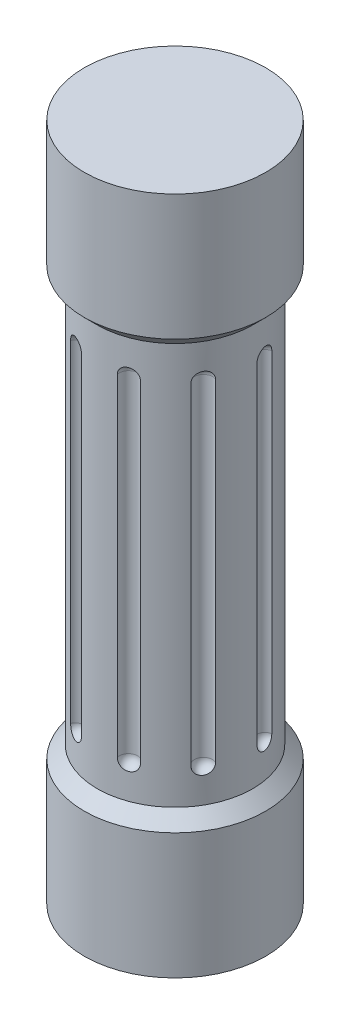
SolidWorks part; units mm, degrees
ref_plane "Front Plane" through (0, 0, 0) normal (0, 0, 1) x (1, 0, 0)
ref_plane "Top Plane" through (0, 0, 0) normal (0, 1, 0) x (1, 0, 0)
ref_plane "Right Plane" through (0, 0, 0) normal (1, 0, 0) x (0, 0, -1)
sketch "Sketch1" plane through (0, 0, 0) normal (0, 0, 1) x (1, 0, 0)
  line L0 (0, 0) -> (0, 26.2)
  line L1 (0, 26.2) -> (3.5, 26.2)
  line L2 (3.5, 26.2) -> (3.5, 23.35)
  line L3 (0, 0) -> (3.5, 0)
  line L4 (3.5, 0) -> (3.5, 2.85)
  line L5 (3.5, 2.85) -> (3.5, 4.85)
  line L6 (0, 26.2) -> (0, 52.4) construction
  line L8 (3, 20.85) -> (3, 5.35)
  line L10 (3, 13.1) -> (0, 13.1) construction
  line L11 (3.5, 23.35) -> (3.5, 21.35)
  line L12 (3.5, 21.35) -> (3.5, 4.85) construction
  line L13 (3.5, 21.35) -> (3, 20.85)
  line L14 (3.5, 4.85) -> (3, 5.35)
  point P3 (0, 13.1)
  dimension "D1" = 20.5
  dimension "D2" = 2.85
  dimension "D3" = 7
  dimension "D4" = 0.5
  dimension "D5" = 2
  dimension "D6" = 45
revolve "Main Support Pole" add sketch "Sketch1" angle 360 about L6
sketch "Sketch2" plane through (0, 0, 0) normal (1, 0, 0) x (0, 0, -1)
  line L0 (3, 19.85) -> (3, 6.35)
  line L3 (2.65, 19.5) -> (2.65, 6.7)
  line L9 (2.65, 13.1) -> (3, 13.1) construction
  line L10 (0, 0) -> (0, 26.2) construction
  line L11 (3.5, 26.2) -> (-3.5, 26.2) construction
  line L12 (3, 5.35) -> (3, 20.85) construction
  line L14 (3, 19.85) -> (3, 46.05) construction
  arc A2 (2.65, 19.5) -> (3, 19.85) centre (3, 19.5) cw
  arc A3 (2.65, 6.7) -> (3, 6.35) centre (3, 6.7) ccw
  point P8 (3, 13.1)
  point P14 (0, 13.1)
  dimension "D1" = 1
  dimension "D2" = 0.35
revolve "Column Cut" cut sketch "Sketch2" angle 360 about L14
pattern_circular "Column Circular Pattern Cut" count 9 over 360 about axis through (0, 0, 0) along (0, 1, 0) of "Column Cut"
equation "\"D1@Sketch1\"=\"A\"-\"a2\""
equation "\"screen width\"= 45.00mm"
equation "\"screen height\"= 85.00mm"
equation "\"top cutoff\" = 2.00mm"
equation "\"A\" = \"screen width\" / 2"
equation "\"B\" = \"screen width\" / 2"
equation "\"screen hypotenuse\" = sqr ( ( \"A\" * \"A\" ) + ( \"B\" * \"B\" ) )"
equation "\"a2\" = \"top cutoff\" "
equation "\"b2\" = \"top cutoff\""
equation "\"top cutoff hypotenuse\" = sqr ( ( \"a2\" * \"a2\" ) + ( \"b2\" * \"b2\" ) )"
equation "\"total hypotenuse\" = \"screen hypotenuse\" - \"top cutoff hypotenuse\""
equation "\"image display width\" = ( \"A\" / 3 ) * 2"
equation "\"image display height\" = ( \"B\" / 3 ) * 2"
equation "\"support pole dia\" = 7.00mm"
equation "\"support pole loose fit hole dia\" = \"support pole dia\"+0.5"
equation "\"support pole tight fit hole dia\" = \"support pole dia\"+0.25"
equation "\"D3@Sketch1\"=\"support pole dia\""
